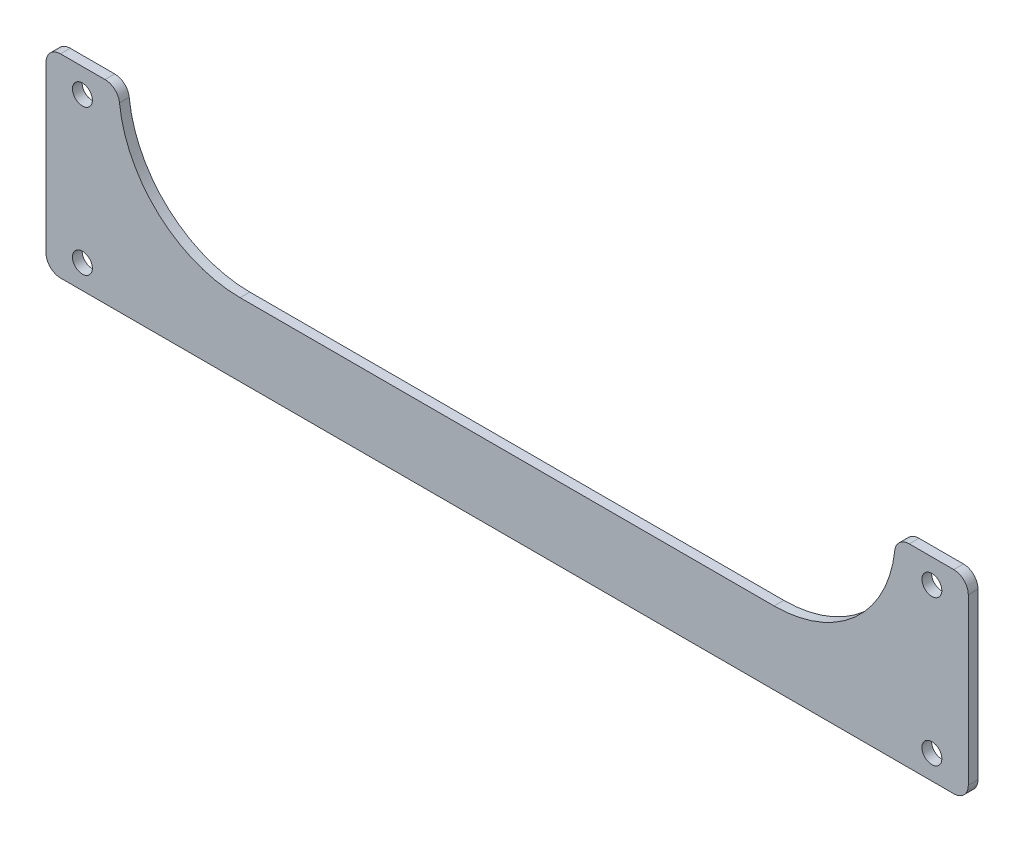
SolidWorks part; units mm, degrees
ref_plane "前视基准面" through (0, 0, 0) normal (0, 0, 1) x (1, 0, 0)
ref_plane "上视基准面" through (0, 0, 0) normal (0, 1, 0) x (1, 0, 0)
ref_plane "右视基准面" through (0, 0, 0) normal (1, 0, 0) x (0, 0, -1)
sketch "草图1" plane through (0, 0, 0) normal (0, 0, 1) x (1, 0, 0)
  line L1 (-95, 20) -> (95, 20)
  line L2 (-95, 20) -> (-95, -20)
  line L3 (-95, -20) -> (95, -20)
  line L4 (95, 20) -> (95, -20)
  line L5 (-95, 20) -> (95, -20) construction
  line L6 (-95, -20) -> (95, 20) construction
  point P0 (0, 0)
  dimension "D1" = 40
  dimension "D2" = 190
extrude "凸台-拉伸1" add sketch "草图1" along normal blind 2
sketch "草图2" plane through (0, 0, 2) normal (0, 0, 1) x (1, 0, 0)
  line L0 (0, 61.505) -> (0, -71.505) construction
  line L1 (55, -5) -> (-55, -5)
  line L2 (-95, -20) -> (95, -20) construction
  line L4 (95, 20) -> (-95, 20) construction
  line L5 (-80, 20) -> (80, 20)
  line L6 (-80, 20) -> (80, 20)
  arc A0 (-55, -5) -> (-80, 20) centre (-55, 20) cw
  arc A1 (55, -5) -> (80, 20) centre (55, 20) ccw
  point P14 (0, 20)
  point P16 (0, -5)
  line M4 (95, 20) -> (-95, 20)
  dimension "D1" = 15
  dimension "D2" = 15
extrude "切除-拉伸1" cut sketch "草图2" against normal blind 2 contours L0 L6 A0 L1 | L0 L1 A1 M4
sketch "草图3" plane through (0, 0, 2) normal (0, 0, 1) x (1, 0, 0)
  line L0 (-95, 20) -> (-95, -20) construction
  line L1 (-80, 20) -> (-95, 20) construction
  line L2 (-95, -20) -> (95, -20) construction
  line L3 (0, 53.0401) -> (0, -67.1883) construction
  circle A0 centre (-87.5, 15) radius 2.05
  circle A1 centre (-87.5, -15) radius 2.05
  circle A2 centre (87.5, -15) radius 2.05
  circle A3 centre (87.5, 15) radius 2.05
  dimension "D1" = 7.5
  dimension "D2" = 4.1
  dimension "D3" = 5
  dimension "D4" = 5
extrude "切除-拉伸2" cut sketch "草图3" against normal blind 2
fillet "圆角1" radius 3 6 edges at (80, 20, 1) (95, -20, 1) (-95, -20, 1) (-95, 20, 1) (-80, 20, 1) (95, 20, 1)
